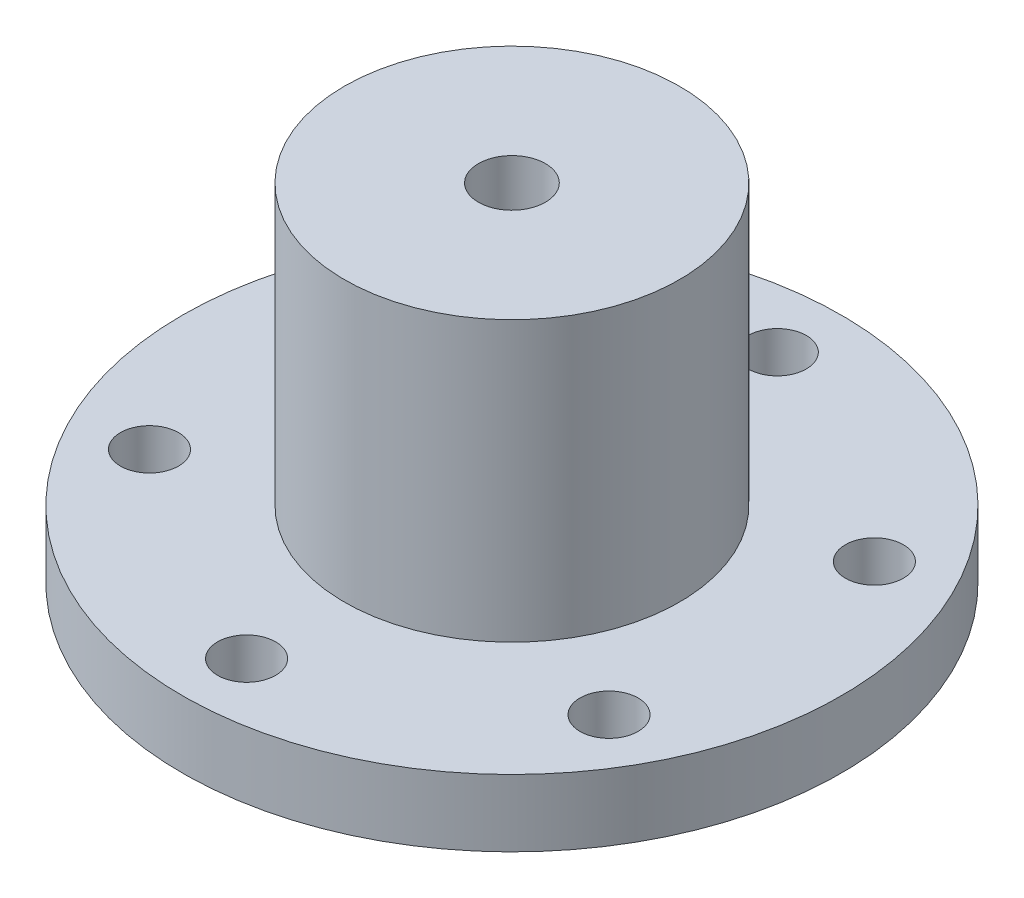
SolidWorks part; units mm, degrees
material "1060 Alloy"
ref_plane "Front Plane" through (0, 0, 0) normal (0, 0, 1) x (1, 0, 0)
ref_plane "Top Plane" through (0, 0, 0) normal (0, 1, 0) x (1, 0, 0)
ref_plane "Right Plane" through (0, 0, 0) normal (1, 0, 0) x (0, 0, -1)
sketch "Sketch1" plane through (0, 0, 0) normal (0, 0, 1) x (1, 0, 0)
  line L0 (0, -15.5) -> (29.5, -15.5)
  line L1 (29.5, -15.5) -> (29.5, -9.5)
  line L2 (29.5, -9.5) -> (15, -9.5)
  line L3 (15, -9.5) -> (15, 15.5)
  line L4 (15, 15.5) -> (0, 15.5)
  line L5 (0, 15.5) -> (0, -15.5)
  line L6 (0, 0) -> (0, -18.7279) construction
  dimension "D1" = 59
  dimension "D2" = 6
  dimension "D3" = 25
  dimension "D4" = 30
revolve "Revolve1" add sketch "Sketch1" angle 360 about L6
sketch "Sketch2" plane through (0, 15.5, 0) normal (0, 1, 0) x (1, 0, 0)
  circle A0 centre (0, 0) radius 23.75 construction
  circle A1 centre (0, 0) radius 3
  circle A2 centre (0, 23.75) radius 2.6
  circle A3 centre (20.5681, 11.875) radius 2.6
  circle A4 centre (20.5681, -11.875) radius 2.6
  circle A5 centre (0, -23.75) radius 2.6
  circle A6 centre (-20.5681, -11.875) radius 2.6
  circle A7 centre (-20.5681, 11.875) radius 2.6
  point P7 (0, 0)
  point P8 (0, 0)
  point P18 (0, 0)
  point P19 (0, 0)
  point P20 (0, 0)
  point P21 (0, 0)
  dimension "D1" = 47.5
  dimension "D2" = 6
  dimension "D3" = 5.2
  dimension "D4" = 6
extrude "Cut-Extrude1" cut sketch "Sketch2" against normal up to next
